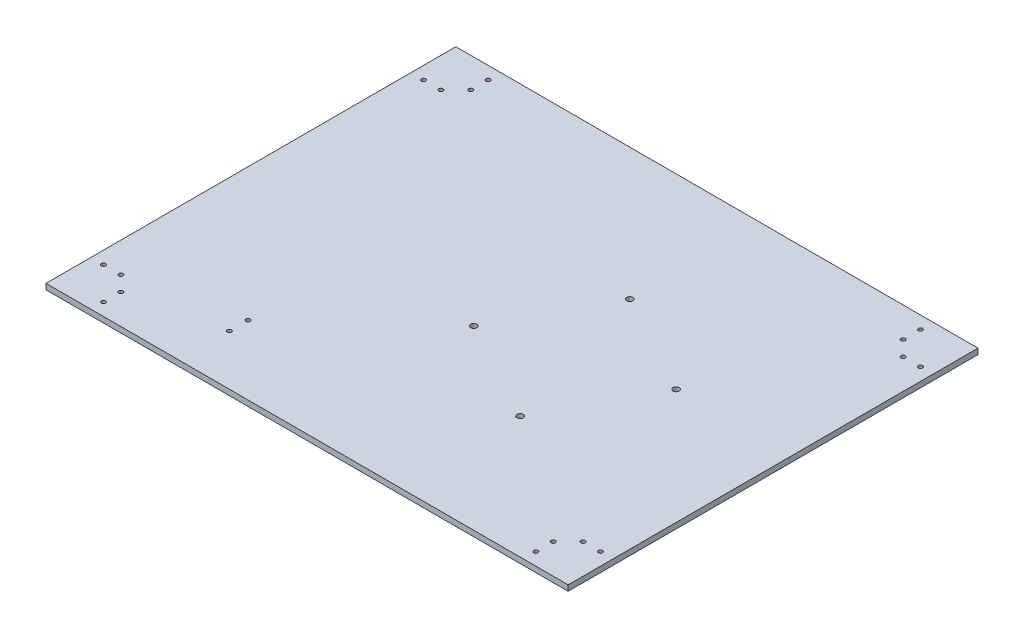
SolidWorks part; units mm, degrees
material "Pino"
ref_plane "Piano frontale" through (0, 0, 0) normal (0, 0, 1) x (1, 0, 0)
ref_plane "Piano superiore" through (0, 0, 0) normal (0, 1, 0) x (1, 0, 0)
ref_plane "Piano destro" through (0, 0, 0) normal (1, 0, 0) x (0, 0, -1)
sketch "Schizzo1" plane through (0, 0, 0) normal (0, 1, 0) x (1, 0, 0)
  line L1 (-279, 219) -> (279, 219)
  line L2 (-279, 219) -> (-279, -219)
  line L3 (-279, -219) -> (279, -219)
  line L4 (279, 219) -> (279, -219)
  line L5 (-279, 219) -> (279, -219) construction
  line L6 (-279, -219) -> (279, 219) construction
  point P4 (0, 0)
  dimension "D1" = 558
  dimension "D2" = 438
extrude "Estrusione-Estrusione1" add sketch "Schizzo1" along normal blind 6
sketch "Schizzo2" plane through (0, 6, 0) normal (0, 1, 0) x (1, 0, 0)
  circle A0 centre (-231, 205.5) radius 2.25
  circle A1 centre (-231, 187) radius 2.25
  circle A2 centre (-247, 171) radius 2.25
  circle A3 centre (-265.5, 171) radius 2.25
  circle A4 centre (231, 205.5) radius 2.25
  circle A5 centre (231, 187) radius 2.25
  circle A6 centre (247, 171) radius 2.25
  circle A7 centre (265.5, 171) radius 2.25
  circle A8 centre (265.5, -171) radius 2.25
  circle A9 centre (247, -171) radius 2.25
  circle A10 centre (231, -187) radius 2.25
  circle A11 centre (231, -205.5) radius 2.25
  circle A12 centre (-231, -205.5) radius 2.25
  circle A13 centre (-231, -187) radius 2.25
  circle A14 centre (-247, -171) radius 2.25
  circle A15 centre (-265.5, -171) radius 2.25
  dimension "D1" = 4.5
extrude "Taglio-Estrusione1" cut sketch "Schizzo2" against normal blind 10
sketch "Schizzo4" plane through (0, 6, 0) normal (0, 1, 0) x (1, 0, 0)
  line L0 (279, -219) -> (279, 219) construction
  line L1 (279, 219) -> (-279, 219) construction
  line L2 (-279, -219) -> (279, -219) construction
  line L3 (-279, 219) -> (-279, -219) construction
  line L4 (-11.0471, -29.9509) -> (72.3592, -5.1397) construction
  line L5 (72.3592, -5.1397) -> (47.5479, 78.2666) construction
  line L6 (72.3592, -5.1397) -> (97.1704, -88.546) construction
  circle A0 centre (-11.0471, -29.9509) radius 3.3
  circle A1 centre (97.1704, -88.546) radius 3.3
  circle A2 centre (155.7655, 19.6716) radius 3.3
  circle A3 centre (47.5479, 78.2666) radius 3.3
  circle A4 centre (72.3592, -5.1397) radius 87.0184 construction
  dimension "D1" = 6.6
  dimension "D3" = 199.3284
  dimension "D4" = 174.0369
  dimension "D2" = 123.2345
  dimension "D5" = 189.0491
  dimension "D6" = 267.9529
  dimension "D7" = 90
extrude "Taglio-Estrusione2" cut sketch "Schizzo4" against normal blind 10
sketch "Schizzo5" plane through (0, 0, 0) normal (0, -1, 0) x (1, 0, 0)
  line L0 (-279, -219) -> (-279, 219) construction
  line L1 (-279, 219) -> (279, 219) construction
  line L2 (-136.9216, 165.1352) -> (-136.9216, 145.1352) construction
  circle A2 centre (-136.9216, 165.1352) radius 2.25
  circle A3 centre (-136.9216, 145.1352) radius 2.25
  dimension "D4" = 4.5
  dimension "D1" = 20
  dimension "D2" = 142.0784
  dimension "D3" = 73.8648
extrude "Taglio-Estrusione3" cut sketch "Schizzo5" against normal blind 10
